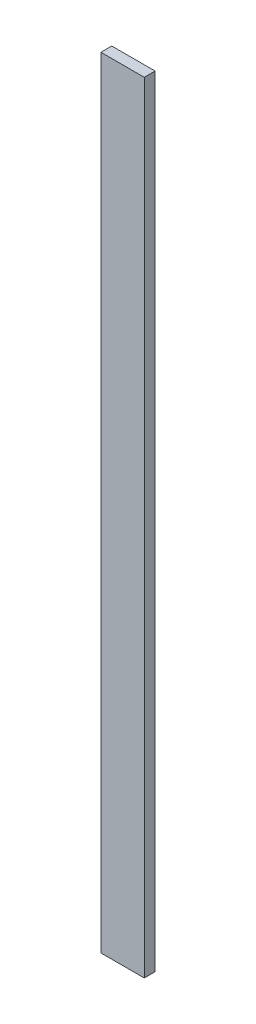
SolidWorks part; units mm, degrees
ref_plane "Front Plane" through (0, 0, 0) normal (0, 0, 1) x (1, 0, 0)
ref_plane "Top Plane" through (0, 0, 0) normal (0, 1, 0) x (1, 0, 0)
ref_plane "Right Plane" through (0, 0, 0) normal (1, 0, 0) x (0, 0, -1)
sketch "Sketch1" plane through (0, 0, 0) normal (0, 0, 1) x (1, 0, 0)
  line L1 (-12.7, -228.6) -> (12.7, -228.6)
  line L2 (-12.7, -228.6) -> (-12.7, 228.6)
  line L3 (-12.7, 228.6) -> (12.7, 228.6)
  line L4 (12.7, -228.6) -> (12.7, 228.6)
  line L5 (-12.7, -228.6) -> (12.7, 228.6) construction
  line L6 (-12.7, 228.6) -> (12.7, -228.6) construction
  point P0 (0, 0)
  dimension "D1" = 457.2
  dimension "D2" = 25.4
extrude "Boss-Extrude1" add sketch "Sketch1" along normal blind 6.35
sketch "Sketch2" [suppressed] plane through (0, 0, 0) normal (0, 0, -1) x (-1, 0, 0)
  line L1 (-14.2875, 114.3) -> (14.2875, 114.3)
  line L2 (-14.2875, 114.3) -> (-14.2875, 38.1)
  line L3 (-14.2875, 38.1) -> (14.2875, 38.1)
  line L4 (14.2875, 114.3) -> (14.2875, 38.1)
  point P5 (0, 114.3)
  dimension "D1" = 28.575
  dimension "D2" = 38.1
  dimension "D3" = 114.3
extrude "Cut-Extrude1" [suppressed] cut sketch "Sketch2" against normal through all
